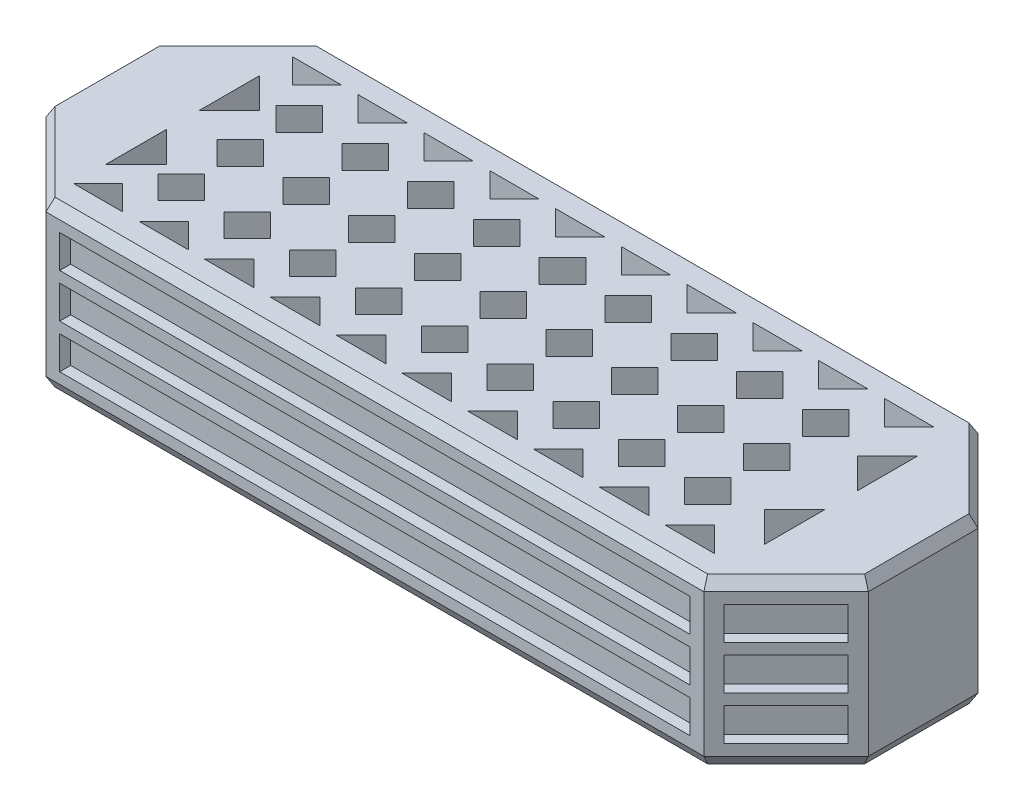
SolidWorks part; units mm, degrees
ref_plane "Front Plane" through (0, 0, 0) normal (0, 0, 1) x (1, 0, 0)
ref_plane "Top Plane" through (0, 0, 0) normal (0, 1, 0) x (1, 0, 0)
ref_plane "Right Plane" through (0, 0, 0) normal (1, 0, 0) x (0, 0, -1)
sketch "Sketch2" plane through (0, 0, 0) normal (0, 1, 0) x (1, 0, 0)
  line L1 (-75, 25) -> (75, 25)
  line L2 (-75, 25) -> (-75, -25)
  line L3 (-75, -25) -> (75, -25)
  line L4 (75, 25) -> (75, -25)
  line L5 (-75, 25) -> (75, -25) construction
  line L6 (-75, -25) -> (75, 25) construction
  point P0 (0, 0)
  dimension "D1" = 150
  dimension "D2" = 50
extrude "Boss-Extrude2" add sketch "Sketch2" along normal blind 30
chamfer "Chamfer1" distance 15 angle 45 4 edges at (-75, 15, -25) (75, 15, -25) (75, 15, 25) (-75, 15, 25)
sketch "Sketch3" plane through (0, 0, 25) normal (0, 0, 1) x (1, 0, 0)
  line L0 (0, 30) -> (0, 0) construction
  line L1 (-57.5, 26) -> (57.5, 26)
  line L2 (-57.5, 26) -> (-57.5, 20)
  line L3 (-57.5, 20) -> (57.5, 20)
  line L4 (-60, 0) -> (60, 0)
  line L5 (60, 0) -> (60, 30)
  line L6 (60, 30) -> (-60, 30)
  line L7 (-60, 30) -> (-60, 0)
  line L8 (-60, 0) -> (60, 0)
  line L9 (60, 0) -> (60, 30)
  line L10 (60, 30) -> (-60, 30)
  line L11 (-60, 30) -> (-60, 0)
  line L12 (57.5, 26) -> (57.5, 20)
  line L13 (-57.5, 26) -> (57.5, 20) construction
  line L14 (-57.5, 20) -> (57.5, 26) construction
  line L15 (-57.5, 18) -> (57.5, 18)
  line L16 (-57.5, 18) -> (-57.5, 12)
  line L17 (-57.5, 12) -> (57.5, 12)
  line L18 (57.5, 18) -> (57.5, 12)
  line L19 (-57.5, 18) -> (57.5, 12) construction
  line L20 (-57.5, 12) -> (57.5, 18) construction
  line L21 (-57.5, 10) -> (57.5, 10)
  line L22 (-57.5, 10) -> (-57.5, 4)
  line L23 (-57.5, 4) -> (57.5, 4)
  line L24 (57.5, 10) -> (57.5, 4)
  line L25 (-57.5, 10) -> (57.5, 4) construction
  line L26 (-57.5, 4) -> (57.5, 10) construction
  point P2 (0, 23)
  point P9 (0, 15)
  point P14 (0, 7)
  point P22 (0, 0)
  point P23 (0, 0)
  point P24 (0, 0)
  dimension "D2" = 6
  dimension "D3" = 115
  dimension "D4" = 115
  dimension "D5" = 6
  dimension "D6" = 115
  dimension "D7" = 6
  dimension "D8" = 4
  dimension "D9" = 4
  dimension "D10" = 2
  dimension "D1" = 0
extrude "Cut-Extrude1" cut sketch "Sketch3" against normal blind 2 contours L12 L1 L2 L3 | L18 L15 L16 L17 | L24 L21 L22 L23
mirror "Mirror1" about plane through (0, 0, 0) normal (0, 0, 1) of "Cut-Extrude1"
sketch "Sketch5" plane through (0, 30, 0) normal (0, 1, 0) x (1, 0, 0)
  line L0 (-60.0503, -20) -> (-51.0207, -20)
  line L1 (-51.0207, -20) -> (-55.5355, -15.4852)
  line L2 (-55.5355, -15.4852) -> (-60.0503, -20)
  line L3 (-43.5355, -15.4852) -> (-48.0503, -20)
  line L4 (-48.0503, -20) -> (-39.0207, -20)
  line L5 (-39.0207, -20) -> (-43.5355, -15.4852)
  line L6 (-31.5355, -15.4852) -> (-36.0503, -20)
  line L7 (-36.0503, -20) -> (-27.0207, -20)
  line L8 (60, 25) -> (-60, 25)
  line L9 (-60, 25) -> (-75, 10)
  line L10 (-75, 10) -> (-75, -10)
  line L11 (-75, -10) -> (-60, -25)
  line L12 (-60, -25) -> (60, -25)
  line L13 (60, -25) -> (75, -10)
  line L14 (75, -10) -> (75, 10)
  line L15 (75, 10) -> (60, 25)
  line L16 (60, 25) -> (-60, 25)
  line L17 (-60, 25) -> (-75, 10)
  line L18 (-75, 10) -> (-75, -10)
  line L19 (-75, -10) -> (-60, -25)
  line L20 (-60, -25) -> (60, -25)
  line L21 (60, -25) -> (75, -10)
  line L22 (75, -10) -> (75, 10)
  line L23 (75, 10) -> (60, 25)
  line L24 (-27.0207, -20) -> (-31.5355, -15.4852)
  line L25 (-19.5355, -15.4852) -> (-24.0503, -20)
  line L26 (-24.0503, -20) -> (-15.0207, -20)
  line L27 (-15.0207, -20) -> (-19.5355, -15.4852)
  line L28 (-7.5355, -15.4852) -> (-12.0503, -20)
  line L29 (-12.0503, -20) -> (-3.0207, -20)
  line L30 (-3.0207, -20) -> (-7.5355, -15.4852)
  line L31 (4.4645, -15.4852) -> (-0.0503, -20)
  line L32 (-0.0503, -20) -> (8.9793, -20)
  line L33 (8.9793, -20) -> (4.4645, -15.4852)
  line L34 (16.4645, -15.4852) -> (11.9497, -20)
  line L35 (11.9497, -20) -> (20.9793, -20)
  line L36 (20.9793, -20) -> (16.4645, -15.4852)
  line L37 (28.4645, -15.4852) -> (23.9497, -20)
  line L38 (23.9497, -20) -> (32.9793, -20)
  line L39 (32.9793, -20) -> (28.4645, -15.4852)
  line L40 (40.4645, -15.4852) -> (35.9497, -20)
  line L41 (35.9497, -20) -> (44.9793, -20)
  line L42 (44.9793, -20) -> (40.4645, -15.4852)
  line L43 (52.4645, -15.4852) -> (47.9497, -20)
  line L44 (47.9497, -20) -> (56.9793, -20)
  line L45 (56.9793, -20) -> (52.4645, -15.4852)
  line L46 (-49.5463, -15) -> (-53.7889, -10.7574)
  line L47 (-53.7889, -10.7574) -> (-49.5463, -6.5147)
  line L48 (-49.5463, -6.5147) -> (-45.3036, -10.7574)
  line L49 (-45.3036, -10.7574) -> (-49.5463, -15)
  line L85 (-37.5463, -15) -> (-41.7889, -10.7574)
  line L86 (-41.7889, -10.7574) -> (-37.5463, -6.5147)
  line L87 (-33.3036, -10.7574) -> (-37.5463, -15)
  line L88 (-37.5463, -6.5147) -> (-33.3036, -10.7574)
  line L89 (-25.5463, -15) -> (-29.7889, -10.7574)
  line L90 (-29.7889, -10.7574) -> (-25.5463, -6.5147)
  line L91 (-21.3036, -10.7574) -> (-25.5463, -15)
  line L92 (-25.5463, -6.5147) -> (-21.3036, -10.7574)
  line L93 (-13.5463, -15) -> (-17.7889, -10.7574)
  line L94 (-17.7889, -10.7574) -> (-13.5463, -6.5147)
  line L95 (-9.3036, -10.7574) -> (-13.5463, -15)
  line L96 (-13.5463, -6.5147) -> (-9.3036, -10.7574)
  line L97 (-1.5463, -15) -> (-5.7889, -10.7574)
  line L98 (-5.7889, -10.7574) -> (-1.5463, -6.5147)
  line L99 (2.6964, -10.7574) -> (-1.5463, -15)
  line L100 (-1.5463, -6.5147) -> (2.6964, -10.7574)
  line L101 (10.4537, -15) -> (6.2111, -10.7574)
  line L102 (6.2111, -10.7574) -> (10.4537, -6.5147)
  line L103 (14.6964, -10.7574) -> (10.4537, -15)
  line L104 (10.4537, -6.5147) -> (14.6964, -10.7574)
  line L105 (22.4537, -15) -> (18.2111, -10.7574)
  line L106 (18.2111, -10.7574) -> (22.4537, -6.5147)
  line L107 (26.6964, -10.7574) -> (22.4537, -15)
  line L108 (22.4537, -6.5147) -> (26.6964, -10.7574)
  line L109 (34.4537, -15) -> (30.2111, -10.7574)
  line L110 (30.2111, -10.7574) -> (34.4537, -6.5147)
  line L111 (38.6964, -10.7574) -> (34.4537, -15)
  line L112 (34.4537, -6.5147) -> (38.6964, -10.7574)
  line L113 (46.4537, -15) -> (42.2111, -10.7574)
  line L114 (42.2111, -10.7574) -> (46.4537, -6.5147)
  line L115 (50.6964, -10.7574) -> (46.4537, -15)
  line L116 (46.4537, -6.5147) -> (50.6964, -10.7574)
  line L117 (-37.5677, -4.2426) -> (-41.8103, 0)
  line L121 (-16.5, 0) -> (16.5, 0) construction
  line L122 (50.6964, 10.7574) -> (46.4537, 15)
  line L123 (46.4537, 6.5147) -> (50.6964, 10.7574)
  line L124 (42.2111, 10.7574) -> (46.4537, 6.5147)
  line L125 (46.4537, 15) -> (42.2111, 10.7574)
  line L126 (38.6964, 10.7574) -> (34.4537, 15)
  line L127 (34.4537, 6.5147) -> (38.6964, 10.7574)
  line L128 (30.2111, 10.7574) -> (34.4537, 6.5147)
  line L129 (34.4537, 15) -> (30.2111, 10.7574)
  line L130 (26.6964, 10.7574) -> (22.4537, 15)
  line L131 (22.4537, 6.5147) -> (26.6964, 10.7574)
  line L132 (18.2111, 10.7574) -> (22.4537, 6.5147)
  line L133 (22.4537, 15) -> (18.2111, 10.7574)
  line L134 (14.6964, 10.7574) -> (10.4537, 15)
  line L135 (10.4537, 6.5147) -> (14.6964, 10.7574)
  line L136 (6.2111, 10.7574) -> (10.4537, 6.5147)
  line L137 (10.4537, 15) -> (6.2111, 10.7574)
  line L138 (2.6964, 10.7574) -> (-1.5463, 15)
  line L139 (-1.5463, 6.5147) -> (2.6964, 10.7574)
  line L140 (-5.7889, 10.7574) -> (-1.5463, 6.5147)
  line L141 (-1.5463, 15) -> (-5.7889, 10.7574)
  line L142 (-9.3036, 10.7574) -> (-13.5463, 15)
  line L143 (-13.5463, 6.5147) -> (-9.3036, 10.7574)
  line L144 (-17.7889, 10.7574) -> (-13.5463, 6.5147)
  line L145 (-13.5463, 15) -> (-17.7889, 10.7574)
  line L146 (-21.3036, 10.7574) -> (-25.5463, 15)
  line L147 (-25.5463, 6.5147) -> (-21.3036, 10.7574)
  line L148 (-29.7889, 10.7574) -> (-25.5463, 6.5147)
  line L149 (-25.5463, 15) -> (-29.7889, 10.7574)
  line L150 (-33.3036, 10.7574) -> (-37.5463, 15)
  line L151 (-37.5463, 6.5147) -> (-33.3036, 10.7574)
  line L152 (-41.7889, 10.7574) -> (-37.5463, 6.5147)
  line L153 (-37.5463, 15) -> (-41.7889, 10.7574)
  line L154 (-49.5463, 6.5147) -> (-45.3036, 10.7574)
  line L155 (-45.3036, 10.7574) -> (-49.5463, 15)
  line L156 (-53.7889, 10.7574) -> (-49.5463, 6.5147)
  line L157 (-49.5463, 15) -> (-53.7889, 10.7574)
  line L158 (56.9793, 20) -> (52.4645, 15.4852)
  line L159 (47.9497, 20) -> (56.9793, 20)
  line L160 (52.4645, 15.4852) -> (47.9497, 20)
  line L161 (44.9793, 20) -> (40.4645, 15.4852)
  line L162 (35.9497, 20) -> (44.9793, 20)
  line L163 (40.4645, 15.4852) -> (35.9497, 20)
  line L164 (32.9793, 20) -> (28.4645, 15.4852)
  line L165 (23.9497, 20) -> (32.9793, 20)
  line L166 (28.4645, 15.4852) -> (23.9497, 20)
  line L167 (20.9793, 20) -> (16.4645, 15.4852)
  line L168 (11.9497, 20) -> (20.9793, 20)
  line L169 (16.4645, 15.4852) -> (11.9497, 20)
  line L170 (8.9793, 20) -> (4.4645, 15.4852)
  line L171 (-0.0503, 20) -> (8.9793, 20)
  line L172 (4.4645, 15.4852) -> (-0.0503, 20)
  line L173 (-3.0207, 20) -> (-7.5355, 15.4852)
  line L174 (-12.0503, 20) -> (-3.0207, 20)
  line L175 (-7.5355, 15.4852) -> (-12.0503, 20)
  line L176 (-15.0207, 20) -> (-19.5355, 15.4852)
  line L177 (-24.0503, 20) -> (-15.0207, 20)
  line L178 (-19.5355, 15.4852) -> (-24.0503, 20)
  line L179 (-27.0207, 20) -> (-31.5355, 15.4852)
  line L180 (-36.0503, 20) -> (-27.0207, 20)
  line L181 (-31.5355, 15.4852) -> (-36.0503, 20)
  line L182 (-39.0207, 20) -> (-43.5355, 15.4852)
  line L183 (-48.0503, 20) -> (-39.0207, 20)
  line L184 (-43.5355, 15.4852) -> (-48.0503, 20)
  line L185 (-51.0207, 20) -> (-55.5355, 15.4852)
  line L186 (-60.0503, 20) -> (-51.0207, 20)
  line L187 (-55.5355, 15.4852) -> (-60.0503, 20)
  line L188 (-75, 0) -> (75, 0) construction
  line L189 (-53.8103, 0) -> (-49.5677, 4.2426)
  line L190 (-49.5677, 4.2426) -> (-45.325, 0)
  line L191 (-45.325, 0) -> (-49.5677, -4.2426)
  line L192 (-49.5677, -4.2426) -> (-53.8103, 0)
  line L193 (-41.8103, 0) -> (-37.5677, 4.2426)
  line L194 (-37.5677, 4.2426) -> (-33.325, 0)
  line L195 (-33.325, 0) -> (-37.5677, -4.2426)
  line L196 (-25.5677, -4.2426) -> (-29.8103, 0)
  line L197 (-29.8103, 0) -> (-25.5677, 4.2426)
  line L198 (-25.5677, 4.2426) -> (-21.325, 0)
  line L199 (-21.325, 0) -> (-25.5677, -4.2426)
  line L200 (-13.5677, -4.2426) -> (-17.8103, 0)
  line L201 (-17.8103, 0) -> (-13.5677, 4.2426)
  line L202 (-13.5677, 4.2426) -> (-9.325, 0)
  line L203 (-9.325, 0) -> (-13.5677, -4.2426)
  line L204 (-1.5677, -4.2426) -> (-5.8103, 0)
  line L205 (-5.8103, 0) -> (-1.5677, 4.2426)
  line L206 (-1.5677, 4.2426) -> (2.675, 0)
  line L207 (2.675, 0) -> (-1.5677, -4.2426)
  line L208 (10.4323, -4.2426) -> (6.1897, 0)
  line L209 (6.1897, 0) -> (10.4323, 4.2426)
  line L210 (10.4323, 4.2426) -> (14.675, 0)
  line L211 (14.675, 0) -> (10.4323, -4.2426)
  line L212 (22.4323, -4.2426) -> (18.1897, 0)
  line L213 (18.1897, 0) -> (22.4323, 4.2426)
  line L214 (22.4323, 4.2426) -> (26.675, 0)
  line L215 (26.675, 0) -> (22.4323, -4.2426)
  line L216 (34.4323, -4.2426) -> (30.1897, 0)
  line L217 (30.1897, 0) -> (34.4323, 4.2426)
  line L218 (34.4323, 4.2426) -> (38.675, 0)
  line L219 (38.675, 0) -> (34.4323, -4.2426)
  line L220 (46.4323, -4.2426) -> (42.1897, 0)
  line L221 (42.1897, 0) -> (46.4323, 4.2426)
  line L222 (46.4323, 4.2426) -> (50.675, 0)
  line L223 (50.675, 0) -> (46.4323, -4.2426)
  line L224 (-60.0503, 14) -> (-60.0503, 3)
  line L225 (-60.0503, 3) -> (-54.5503, 8.5)
  line L226 (-54.5503, 8.5) -> (-60.0503, 14)
  line L227 (-60.0503, -3) -> (-54.5503, -8.5)
  line L228 (-60.0503, -14) -> (-60.0503, -3)
  line L229 (-54.5503, -8.5) -> (-60.0503, -14)
  line L230 (0, -16.5) -> (0, 16.5) construction
  line L231 (60.0503, -14) -> (60.0503, -3)
  line L232 (54.5503, -8.5) -> (60.0503, -14)
  line L233 (60.0503, -3) -> (54.5503, -8.5)
  line L234 (60.0503, 3) -> (54.5503, 8.5)
  line L235 (60.0503, 14) -> (60.0503, 3)
  line L236 (54.5503, 8.5) -> (60.0503, 14)
  point P182 (-54.8993, 7.6896)
  dimension "D2" = 45
  dimension "D3" = 45
  dimension "D4" = 5
  dimension "D5" = 3.5
  dimension "D6" = 6.3848
  dimension "D8" = 6
  dimension "D9" = 6
  dimension "D10" = 10
  dimension "D11" = 9
  dimension "D12" = 9
  dimension "D13" = 45
  dimension "D14" = 45
  dimension "D15" = 3
  dimension "D16" = 6
  dimension "D1" = 0
  dimension "D7" = 10
extrude "Cut-Extrude3" cut sketch "Sketch5" against normal up to next (30 mm away) contours L231 L233 L232 | L236 L234 L235 | L122 L125 L124 L123 | L229 L227 L228 | L225 L226 L224 | L187 L185 L186 | L178 L176 L177 | L172 L170 L171 | L169 L167 L168 | L166 L164 L165 | L163 L161 L162 | L126 L129 L128 L127 | L130 L133 L132 L131 | L134 L137 L136 L135 | L138 L141 L140 L139 | L142 L145 L144 L143 | L146 L149 L148 L147 | L150 L153 L152 L151 | L155 L157 L156 L154 | L188 L192 L191 | L189 L188 L190 | L49 L48 L47 L46 | L1 L2 L0 | L4 L5 L3 | L88 L86 L85 L87 | L7 L24 L6 | L26 L27 L25 | L44 L45 L43 | L116 L114 L113 L115 | L38 L39 L37 | L108 L106 L105 L107 | L35 L36 L34 | L104 L102 L101 L103 | L112 L110 L109 L111 | L96 L94 L93 L95 | L92 L90 L89 L91 | L29 L30 L28 | L32 L33 L31 | L100 L98 L97 L99 | L188 L204 L207 | L205 L188 L206 | L188 L220 L223 | L221 L188 L222 | L217 L188 L218 | L188 L216 L219 | L213 L188 L214 | L188 L212 L215 | L193 L188 L194 | L188 L117 L195 | L197 L188 L198 | L188 L196 L199 | L188 L200 L203 | L201 L188 L202 | L209 L188 L210 | L188 L208 L211 | L183 L182 L184 | L180 L179 L181 | L175 L174 L173 | L159 L158 L160 | L41 L42 L40
sketch "Sketch4" plane through (-42.5, 0, 42.5) normal (-0.7071, 0, 0.7071) x (0.7071, 0, 0.7071)
  line L0 (-35.3553, 30) -> (-35.3553, 0) construction
  line L4 (-24.7487, 30) -> (-45.9619, 30)
  line L5 (-45.9619, 30) -> (-45.9619, 0)
  line L6 (-45.9619, 0) -> (-24.7487, 0)
  line L7 (-24.7487, 0) -> (-24.7487, 30)
  line L8 (-24.7487, 30) -> (-45.9619, 30)
  line L9 (-45.9619, 30) -> (-45.9619, 0)
  line L10 (-45.9619, 0) -> (-24.7487, 0)
  line L11 (-24.7487, 0) -> (-24.7487, 30)
  line L12 (-43.3553, 26) -> (-27.3553, 26)
  line L15 (-43.3553, 26) -> (-43.3553, 20)
  line L18 (-43.3553, 20) -> (-27.3553, 20)
  line L19 (-27.3553, 26) -> (-27.3553, 20)
  line L20 (-43.3553, 26) -> (-27.3553, 20) construction
  line L21 (-43.3553, 20) -> (-27.3553, 26) construction
  line L22 (-43.3553, 18) -> (-27.3553, 18)
  line L23 (-43.3553, 18) -> (-43.3553, 12)
  line L24 (-43.3553, 12) -> (-27.3553, 12)
  line L25 (-27.3553, 18) -> (-27.3553, 12)
  line L26 (-43.3553, 18) -> (-27.3553, 12) construction
  line L27 (-43.3553, 12) -> (-27.3553, 18) construction
  line L28 (-43.3553, 10) -> (-27.3553, 10)
  line L29 (-43.3553, 10) -> (-43.3553, 4)
  line L30 (-43.3553, 4) -> (-27.3553, 4)
  line L31 (-27.3553, 10) -> (-27.3553, 4)
  line L32 (-43.3553, 10) -> (-27.3553, 4) construction
  line L33 (-43.3553, 4) -> (-27.3553, 10) construction
  point P6 (-35.3553, 23)
  point P11 (-35.3553, 15)
  point P16 (-35.3553, 0)
  point P17 (-35.3553, 7)
  point P22 (-35.3553, 22.3144)
  dimension "D3" = 4
  dimension "D7" = 16
  dimension "D9" = 16
  dimension "D2" = 6
  dimension "D4" = 6
  dimension "D5" = 4
  dimension "D6" = 6
  dimension "D8" = 16
  dimension "D1" = 0
extrude "Cut-Extrude5" cut sketch "Sketch4" against normal blind 2 contours L31 L28 L29 L30 | L25 L22 L23 L24 | L19 L12 L15 L18
mirror "Mirror4" about plane through (0, 0, 0) normal (0, 0, 1) of "Cut-Extrude5"
mirror "Mirror5" about plane through (0, 0, 0) normal (1, 0, 0) of "Cut-Extrude5", "Mirror4"
chamfer "Chamfer2" distance 2 angle 30 16 edges at (67.5, 30, -17.5) (75, 30, 0) (67.5, 30, 17.5) (0, 30, 25) (-67.5, 30, 17.5) (-75, 30, 0) (-67.5, 30, -17.5) (0, 30, -25) (0, 0, 25) (-67.5, 0, 17.5) (-75, 0, 0) (-67.5, 0, -17.5) (0, 0, -25) (67.5, 0, -17.5) (75, 0, 0) (67.5, 0, 17.5)
